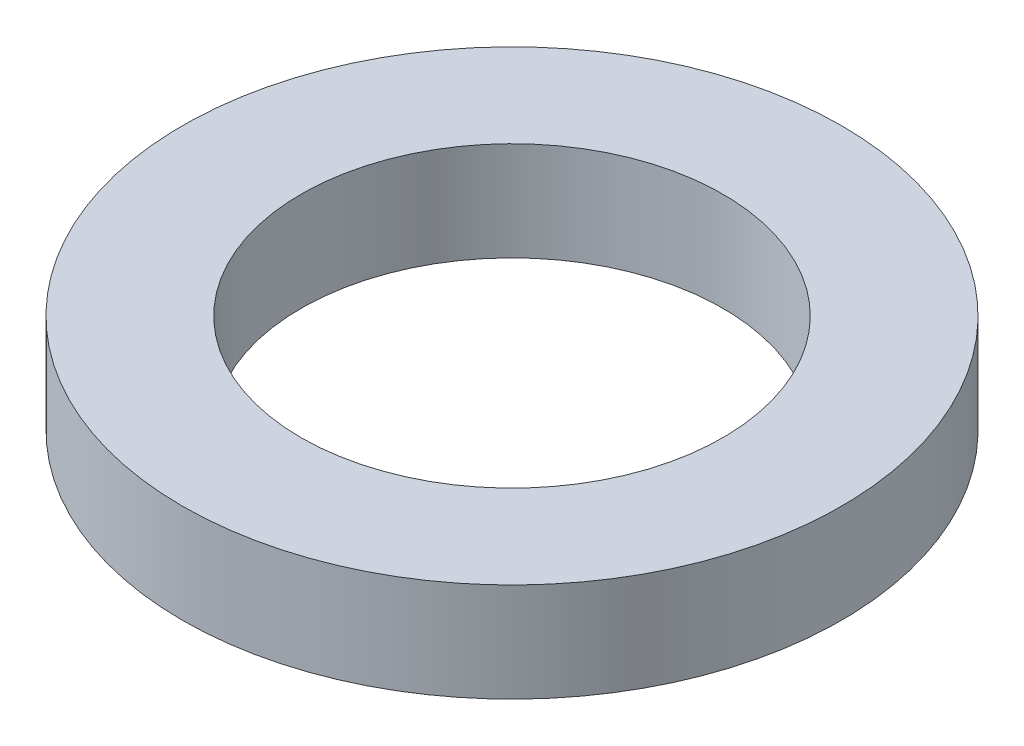
SolidWorks part; units mm, degrees
material "Acier allié"
ref_plane "Plan de face" through (0, 0, 0) normal (0, 0, 1) x (1, 0, 0)
ref_plane "Plan de dessus" through (0, 0, 0) normal (0, 1, 0) x (1, 0, 0)
ref_plane "Plan de droite" through (0, 0, 0) normal (1, 0, 0) x (0, 0, -1)
sketch "Esquisse1" plane through (0, 0, 0) normal (0, 1, 0) x (1, 0, 0)
  circle A0 centre (0, 0) radius 5
  circle A1 centre (0, 0) radius 3.2
  dimension "D1" = 10
  dimension "D2" = 6.4
extrude "Boss.-Extru.1" add sketch "Esquisse1" along normal blind 1.5
